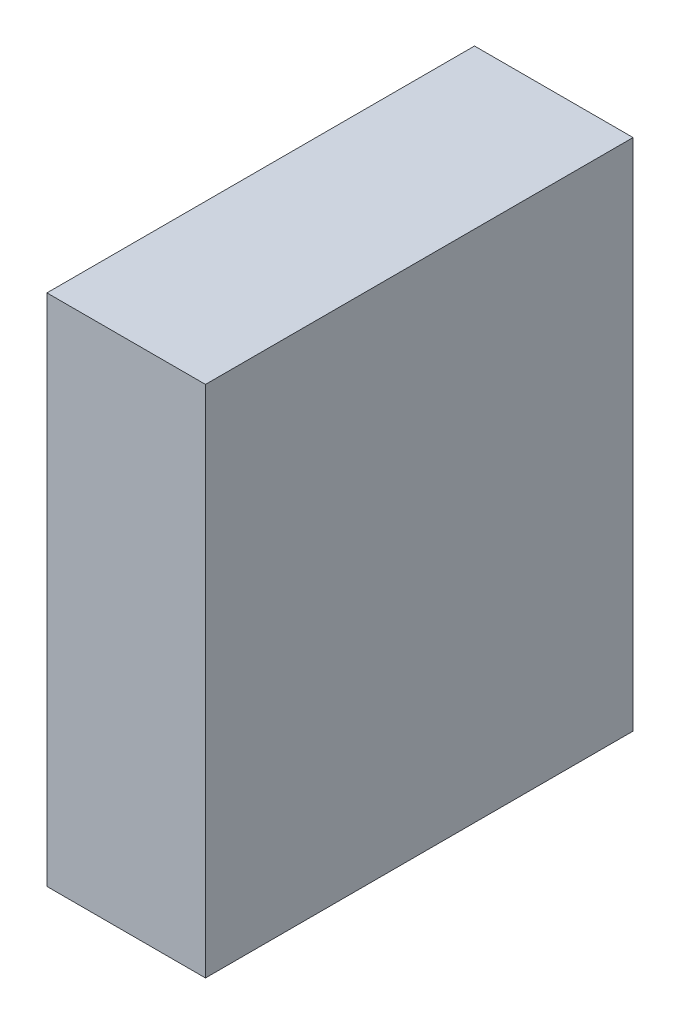
SolidWorks part; units mm, degrees
ref_plane "Front Plane" through (0, 0, 0) normal (0, 0, 1) x (1, 0, 0)
ref_plane "Top Plane" through (0, 0, 0) normal (0, 1, 0) x (1, 0, 0)
ref_plane "Right Plane" through (0, 0, 0) normal (1, 0, 0) x (0, 0, -1)
sketch "Sketch1" plane through (0, 0, 0) normal (0, 0, 1) x (1, 0, 0)
  line L1 (-16.5, 53.5) -> (16.5, 53.5)
  line L2 (-16.5, 53.5) -> (-16.5, -53.5)
  line L3 (-16.5, -53.5) -> (16.5, -53.5)
  line L4 (16.5, 53.5) -> (16.5, -53.5)
  line L5 (-16.5, 53.5) -> (16.5, -53.5) construction
  line L6 (-16.5, -53.5) -> (16.5, 53.5) construction
  point P0 (0, 0)
  dimension "D1" = 33
  dimension "D2" = 107
extrude "Boss-Extrude1" add sketch "Sketch1" along normal blind 89
